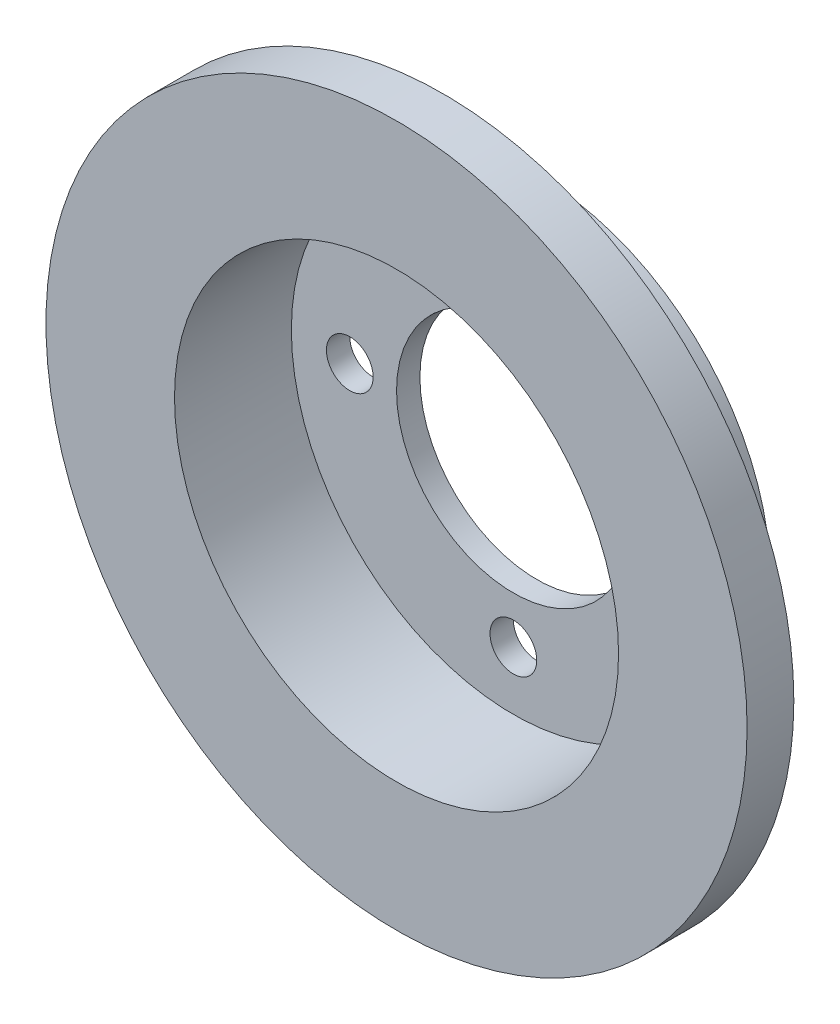
SolidWorks part; units mm, degrees
ref_plane "Front Plane" through (0, 0, 0) normal (0, 0, 1) x (1, 0, 0)
ref_plane "Top Plane" through (0, 0, 0) normal (0, 1, 0) x (1, 0, 0)
ref_plane "Right Plane" through (0, 0, 0) normal (1, 0, 0) x (0, 0, -1)
sketch "Sketch1" plane through (0, 0, 0) normal (0, 0, 1) x (1, 0, 0)
  circle A0 centre (0, 0) radius 50
  dimension "D1" = 100
extrude "Boss-Extrude1" add sketch "Sketch1" along normal blind 20
sketch "Sketch3" plane through (0, 0, 20) normal (0, 0, 1) x (1, 0, 0)
  circle A0 centre (0, 0) radius 75
  dimension "D1" = 150
extrude "Boss-Extrude2" add sketch "Sketch3" along normal blind 10
sketch "Sketch4" plane through (0, 0, 30) normal (0, 0, 1) x (1, 0, 0)
  circle A0 centre (0, 0) radius 47.5
  dimension "D1" = 95
extrude "Cut-Extrude3" cut sketch "Sketch4" against normal blind 25
sketch "Sketch5" plane through (0, 0, 5) normal (0, 0, 1) x (1, 0, 0)
  circle A0 centre (0, 0) radius 25
  dimension "D1" = 50
extrude "Cut-Extrude4" cut sketch "Sketch5" against normal blind 25
sketch "Sketch6" plane through (0, 0, 5) normal (0, 0, 1) x (1, 0, 0)
  line L0 (-46.782, 0) -> (47.5, 0) construction
  line L1 (0, 47.5) -> (0, -47.5) construction
  circle A0 centre (0, 0) radius 47.5 construction
  circle A1 centre (0, 0) radius 47.5 construction
  circle A2 centre (0, 35) radius 5
  circle A3 centre (0, 0) radius 25 construction
  circle A4 centre (35, 0) radius 5
  circle A5 centre (0, -35) radius 5
  circle A6 centre (-35, 0) radius 5
  point P22 (0, 0)
  dimension "D1" = 10
  dimension "D3" = 4
  dimension "D2" = 35
extrude "Cut-Extrude5" cut sketch "Sketch6" against normal blind 25
